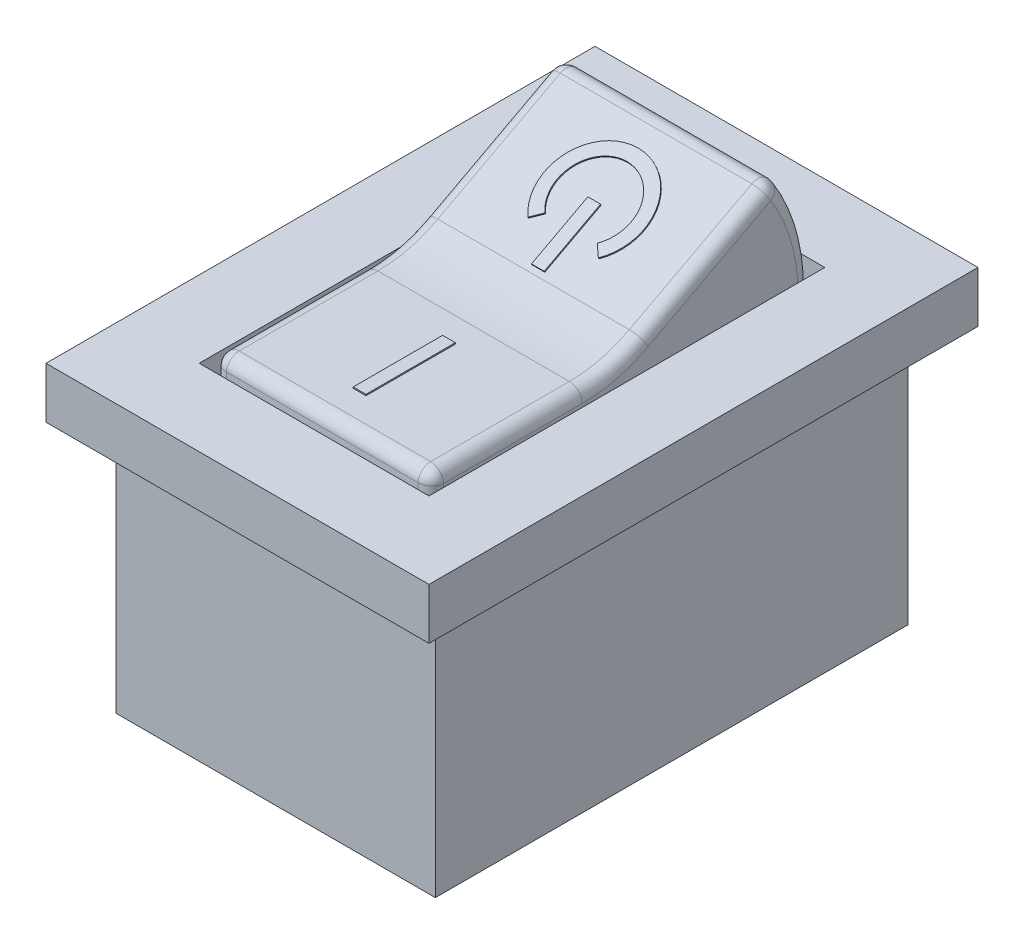
SolidWorks part; units mm, degrees
ref_plane "Front Plane" through (0, 0, 0) normal (0, 0, 1) x (1, 0, 0)
ref_plane "Top Plane" through (0, 0, 0) normal (0, 1, 0) x (1, 0, 0)
ref_plane "Right Plane" through (0, 0, 0) normal (1, 0, 0) x (0, 0, -1)
sketch "Sketch1" plane through (0, 0, 0) normal (0, 1, 0) x (1, 0, 0)
  line L1 (-6.25, 9.25) -> (6.25, 9.25)
  line L2 (-6.25, 9.25) -> (-6.25, -9.25)
  line L3 (-6.25, -9.25) -> (6.25, -9.25)
  line L4 (6.25, 9.25) -> (6.25, -9.25)
  line L5 (-6.25, 9.25) -> (6.25, -9.25) construction
  line L6 (-6.25, -9.25) -> (6.25, 9.25) construction
  point P0 (0, 0)
  dimension "D1" = 12.5
  dimension "D2" = 18.5
extrude "Boss-Extrude1" add sketch "Sketch1" against normal blind 10
sketch "Sketch2" plane through (0, 0, 0) normal (0, 1, 0) x (1, 0, 0)
  line L1 (-7.5, 10.75) -> (7.5, 10.75)
  line L2 (-7.5, 10.75) -> (-7.5, -10.75)
  line L3 (-7.5, -10.75) -> (7.5, -10.75)
  line L4 (7.5, 10.75) -> (7.5, -10.75)
  line L5 (-7.5, 10.75) -> (7.5, -10.75) construction
  line L6 (-7.5, -10.75) -> (7.5, 10.75) construction
  point P0 (0, 0)
  dimension "D1" = 21.5
  dimension "D2" = 15
extrude "Boss-Extrude2" add sketch "Sketch2" along normal blind 2
sketch "Sketch3" plane through (0, 2, 0) normal (0, 1, 0) x (1, 0, 0)
  line L1 (-4.5, 7.75) -> (4.5, 7.75)
  line L2 (-4.5, 7.75) -> (-4.5, -7.75)
  line L3 (-4.5, -7.75) -> (4.5, -7.75)
  line L4 (4.5, 7.75) -> (4.5, -7.75)
  line L5 (-4.5, 7.75) -> (4.5, -7.75) construction
  line L6 (-4.5, -7.75) -> (4.5, 7.75) construction
  point P0 (0, 0)
  dimension "D1" = 15.5
  dimension "D2" = 9
extrude "Cut-Extrude1" cut sketch "Sketch3" against normal blind 11
sketch "Sketch4" plane through (0, 0, 0) normal (1, 0, 0) x (0, 0, -1)
  line L0 (-7.384, 2.3827) -> (-0.2555, 2.3827)
  line L1 (-0.2555, 2.3827) -> (6.0391, 5.7282)
  line L2 (-7.75, 2.3827) -> (6.3623, 5.9) construction
  line L3 (-0.6938, 4.1413) -> (0, 1.3575) construction
  arc A0 (-7.384, 2.3827) -> (6.0391, 5.7282) centre (0, 1.3575) ccw
extrude "Boss-Extrude3" add sketch "Sketch4" along normal mid plane 8.5 separate body
fillet "Fillet1" radius 5 1 edges at (0, 2.3827, 0.2555)
fillet "Fillet2" radius 0.5 10 edges at (4.25, -5.876, -1.8029) (-4.25, -5.876, -1.8029) (0, 5.7282, -6.0391) (4.25, 4.3479, -3.442) (-4.25, 4.3479, -3.442) (-4.25, 2.5311, 0.2925) (4.25, 2.5311, 0.2925) (0, 2.3827, 7.384) (-4.25, 2.3827, 4.4428) (4.25, 2.3827, 4.4428)
sketch "Sketch6" plane through (0, 2.3827, 0) normal (0, 1, 0) x (1, 0, 0)
  line L0 (-3.75, -4.2183) -> (3.75, -4.2183) construction
  line L1 (-3.75, -1.5017) -> (-3.75, -6.9349) construction
  line L2 (3.75, -6.9349) -> (3.75, -1.5017) construction
  line L4 (-0.25, -2.4683) -> (0.25, -2.4683)
  line L5 (-0.25, -2.4683) -> (-0.25, -5.9683)
  line L6 (-0.25, -5.9683) -> (0.25, -5.9683)
  line L7 (0.25, -2.4683) -> (0.25, -5.9683)
  line L8 (-0.25, -2.4683) -> (0.25, -5.9683) construction
  line L9 (-0.25, -5.9683) -> (0.25, -2.4683) construction
  point P6 (0, -4.2183)
  dimension "D1" = 0.5
  dimension "D2" = 3.5
extrude "Boss-Extrude4" add sketch "Sketch6" along normal blind 0.05
sketch "Sketch7" plane through (0, 1.9637, 1.0437) normal (0, 0.883, 0.4693) x (1, 0, 0)
  line L0 (-3.75, 4.8554) -> (3.75, 4.8554) construction
  line L1 (-3.75, 7.572) -> (-3.75, 2.1388) construction
  line L2 (3.75, 2.1388) -> (3.75, 7.572) construction
  line L3 (0, 4.8554) -> (0, 2.6528) construction
  line L4 (-1.0267, 3.8288) -> (-1.3802, 3.4752)
  line L5 (1.0267, 3.8288) -> (1.3802, 3.4752)
  line L7 (-0.25, 4.8554) -> (0.25, 4.8554)
  line L8 (-0.25, 4.8554) -> (-0.25, 2.3554)
  line L9 (-0.25, 2.3554) -> (0.25, 2.3554)
  line L10 (0.25, 4.8554) -> (0.25, 2.3554)
  line L11 (-0.25, 4.8554) -> (0.25, 2.3554) construction
  line L12 (-0.25, 2.3554) -> (0.25, 4.8554) construction
  arc A0 (1.0267, 3.8288) -> (-1.0267, 3.8288) centre (0, 4.8554) ccw
  arc A1 (1.3802, 3.4752) -> (-1.3802, 3.4752) centre (0, 4.8554) ccw
  circle A2 centre (0, 4.8554) radius 1.9519 construction
  circle A3 centre (0, 4.8554) radius 1.4519 construction
  point P16 (0, 3.6054)
  dimension "D2" = 0.5
  dimension "D3" = 2.5
  dimension "D1" = 0.5
extrude "Boss-Extrude5" add sketch "Sketch7" along normal blind 0.05
